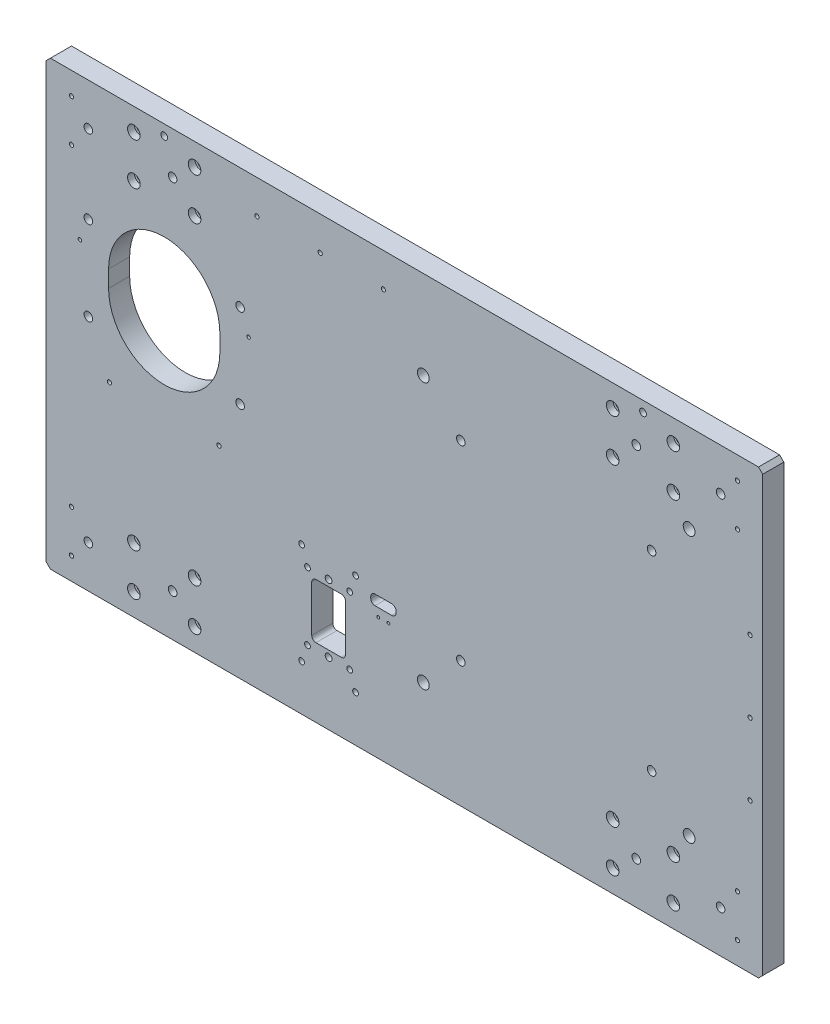
SolidWorks part; units mm, degrees
material "一般碳鋼"
ref_plane "前基準面" through (0, 0, 0) normal (0, 0, 1) x (1, 0, 0)
ref_plane "上基準面" through (0, 0, 0) normal (0, 1, 0) x (1, 0, 0)
ref_plane "右基準面" through (0, 0, 0) normal (1, 0, 0) x (0, 0, -1)
sketch "草圖1" plane through (0, 0, 0) normal (0, 0, 1) x (1, 0, 0)
  line L0 (0, 128.8443) -> (0, 0) construction
  line L1 (-605, 262.5) -> (245, 262.5)
  line L2 (-605, 262.5) -> (-605, -262.5)
  line L3 (-605, -262.5) -> (245, -262.5)
  line L4 (245, 262.5) -> (245, -262.5)
  line L5 (0, 0) -> (107.875, 0) construction
  dimension "D1" = 525
  dimension "D2" = 850
  dimension "D3" = 245
extrude "伸長1" add sketch "草圖1" along normal blind 25
hole_wizard "M16 螺紋孔1" positions "草圖4" profile "草圖3" tap size "M16" standard "GB"
sketch "草圖4" plane through (0, 0, 25) normal (0, 0, 1) x (1, 0, 0)
  line L1 (0, 0) -> (-181.3722, 181.3722) construction
  line L3 (0, 0) -> (0, 223) construction
  circle A0 centre (0, 0) radius 223
  point P1 (-157.6848, 157.6848)
  point P49 (257.6848, 137.6848)
  point P59 (157.6848, 157.6848)
  point P61 (157.6848, -157.6848)
  point P62 (-157.6848, -157.6848)
  dimension "D2" = 446
  dimension "D1" = 45
sketch "草圖3" plane through (-157.6848, 157.6848, 25) normal (1, 0, 0) x (0, -1, 0)
  line L0 (0, 0) -> (0, 42.206)
  line L1 (0, 42.206) -> (7, 38)
  line L2 (7, 38) -> (7, 0)
  line L5 (7, 0) -> (0, 0)
  line L10 (0, 42.206) -> (-7, 38) construction
  line L11 (0, -6.35) -> (0, 107.95) construction
  dimension "螺孔鑽直徑" = 14
  dimension "螺孔鑽深度" = 38
  dimension "導頭角度" = 118
cosmetic thread "鑽孔螺紋1" parameters "D1"=32, "D2"=16
cosmetic thread "鑽孔螺紋2" parameters "D1"=32, "D2"=16
cosmetic thread "鑽孔螺紋3" parameters "D1"=32, "D2"=16
cosmetic thread "鑽孔螺紋4" parameters "D1"=32, "D2"=16
hole_wizard "M12 螺紋孔2" positions "草圖51" profile "草圖50" tap size "M12" standard "GB" end condition up to next
sketch "草圖51" plane through (0, 0, 25) normal (0, 0, 1) x (1, 0, 0)
  line L0 (0, 0) -> (0, 119.7033) construction
  line L2 (0, 0) -> (-71.5063, 71.5063) construction
  circle A0 centre (0, 0) radius 160 construction
  point P1 (-113.1371, 113.1371)
  point P3 (113.1371, 113.1371)
  point P5 (-113.1371, -113.1371)
  point P7 (113.1371, -113.1371)
  dimension "D1" = 320
  dimension "D2" = 45
sketch "草圖50" plane through (-113.1371, 113.1371, 25) normal (1, 0, 0) x (0, -1, 0)
  line L0 (0, 0) -> (0, 25)
  line L1 (0, 25) -> (5.1, 25)
  line L2 (5.1, 25) -> (5.1, 0)
  line L5 (5.1, 0) -> (0, 0)
  line L11 (0, -6.35) -> (0, 107.95) construction
  dimension "貫穿螺孔鑽直徑" = 10.2
  dimension "貫穿螺孔鑽深度" = 25
cosmetic thread "鑽孔螺紋15" parameters "D2"=12
cosmetic thread "鑽孔螺紋16" parameters "D2"=12
cosmetic thread "鑽孔螺紋17" parameters "D2"=12
cosmetic thread "鑽孔螺紋18" parameters "D2"=12
hole_wizard "M8 六角承窩頭蓋螺釘的柱孔1" positions "草圖40" profile "草圖39" counterbore size "M8" standard "ISO" end condition through all
sketch "草圖40" plane through (0, 0, 25) normal (0, 0, 1) x (1, 0, 0)
  line L2 (-605, 0) -> (-201.2497, 0) construction
  line L3 (-605, 262.5) -> (-605, -262.5) construction
  line L5 (0, 0) -> (0, 249.5) construction
  point P1 (-501, 236)
  point P3 (-429, 236)
  point P5 (-501, 186)
  point P7 (-429, 186)
  point P22 (-429, -186)
  point P23 (-501, -186)
  point P24 (-429, -236)
  point P25 (-501, -236)
  dimension "D1" = 72
  dimension "D2" = 50
  dimension "D3" = 422
  dimension "D4" = 429
  dimension "D5" = 50
sketch "草圖39" plane through (-501, 236, 25) normal (1, 0, 0) x (0, -1, 0)
  line L0 (0, 0) -> (0, 25)
  line L1 (0, 25) -> (4.5, 25)
  line L3 (4.5, 25) -> (4.5, 8)
  line L4 (4.5, 8) -> (7.5, 8)
  line L5 (7.5, 8) -> (7.5, 0)
  line L7 (7.5, 0) -> (0, 0)
  line L11 (0, -6.35) -> (0, 107.95) construction
  dimension "貫穿孔直徑" = 9
  dimension "貫穿孔深度" = 25
  dimension "柱孔直徑" = 15
  dimension "柱孔深度" = 8
pattern_linear "直線複製排列1" count 2 spacing 568 along (1, 0, 0) of "M8 六角承窩頭蓋螺釘的柱孔1"
sketch "草圖41" plane through (0, 0, 25) normal (0, 0, 1) x (1, 0, 0)
  line L0 (-465, 80.5) -> (-465, 60.5) construction
  line L2 (-531, 80.5) -> (-531, 60.5)
  line L3 (-605, 262.5) -> (-605, -262.5) construction
  line L4 (-399, 80.5) -> (-399, 60.5)
  line L5 (-465, 174) -> (-465, 105.3673) construction
  line L6 (245, 262.5) -> (-605, 262.5) construction
  line L9 (-260, 70.5) -> (-220.5024, 70.5) construction
  arc A0 (-531, 80.5) -> (-399, 80.5) centre (-465, 80.5) cw
  arc A1 (-531, 60.5) -> (-399, 60.5) centre (-465, 60.5) ccw
  point P0 (-465, 70.5)
  dimension "D1" = 140
  dimension "D2" = 192
  dimension "D5" = 20
  dimension "D6" = 66
  dimension "D7" = 66
extrude "除料-伸長1" cut sketch "草圖41" against normal up to next
chamfer "導角1" distance 5 angle 45 4 edges at (-605, 262.5, 12.5) (245, 262.5, 12.5) (245, -262.5, 12.5) (-605, -262.5, 12.5)
hole_wizard "Ø5.0 (5) 直徑孔1" positions "草圖47" profile "草圖46" hole size "Ø5.0" standard "ISO" end condition up to next
sketch "草圖47" plane through (0, 0, 25) normal (0, 0, 1) x (1, 0, 0)
  line L1 (-501, 236) -> (-429, 236) construction
  line L13 (67, 236) -> (139, 236) construction
  point P0 (-465, 250)
  point P34 (103, 250)
  point P78 (103, 236)
  point P79 (-465, 236)
  dimension "D1" = 14
sketch "草圖46" plane through (-465, 250, 25) normal (1, 0, 0) x (0, -1, 0)
  line L0 (0, 0) -> (0, 25)
  line L1 (0, 25) -> (4, 25)
  line L2 (4, 25) -> (4, 0)
  line L5 (4, 0) -> (0, 0)
  line L11 (0, -6.35) -> (0, 107.95) construction
  dimension "貫穿孔直徑" = 8
  dimension "貫穿孔深度" = 25
hole_wizard "M6 螺紋孔2" positions "草圖55" profile "草圖54" tap size "M6" standard "GB" end condition up to next
sketch "草圖55" plane through (0, 0, 25) normal (0, 0, 1) x (1, 0, 0)
  line L2 (240, 262.5) -> (-600, 262.5) construction
  line L3 (-530, -35.5) -> (-400, -35.5) construction
  line L5 (-605, 257.5) -> (-605, -257.5) construction
  point P0 (-530, -35.5)
  point P1 (-400, -35.5)
  point P22 (-465, -35.5)
  dimension "D1" = 130
  dimension "D2" = 140
  dimension "D5" = 298
sketch "草圖54" plane through (-530, -35.5, 25) normal (1, 0, 0) x (0, -1, 0)
  line L0 (0, 0) -> (0, 25)
  line L1 (0, 25) -> (2.5, 25)
  line L2 (2.5, 25) -> (2.5, 0)
  line L5 (2.5, 0) -> (0, 0)
  line L11 (0, -6.35) -> (0, 107.95) construction
  dimension "貫穿螺孔鑽直徑" = 5
  dimension "貫穿螺孔鑽深度" = 25
cosmetic thread "鑽孔螺紋34" parameters "D2"=6
cosmetic thread "鑽孔螺紋35" parameters "D2"=6
hole_wizard "M6 螺紋孔3" positions "草圖65" profile "草圖64" tap size "M6" standard "GB" end condition up to next
sketch "草圖65" plane through (0, 0, 25) normal (0, 0, 1) x (1, 0, 0)
  line L0 (245, -257.5) -> (245, 257.5) construction
  line L2 (167.2421, 0) -> (230, 0) construction
  point P0 (230, 85)
  point P1 (230, -85)
  point P19 (230, 0)
  dimension "D1" = 15
  dimension "D2" = 170
sketch "草圖64" plane through (230, 85, 25) normal (1, 0, 0) x (0, -1, 0)
  line L0 (0, 0) -> (0, 25)
  line L1 (0, 25) -> (2.5, 25)
  line L2 (2.5, 25) -> (2.5, 0)
  line L5 (2.5, 0) -> (0, 0)
  line L11 (0, -6.35) -> (0, 107.95) construction
  dimension "貫穿螺孔鑽直徑" = 5
  dimension "貫穿螺孔鑽深度" = 25
cosmetic thread "鑽孔螺紋31" parameters "D2"=6
cosmetic thread "鑽孔螺紋32" parameters "D2"=6
cosmetic thread "鑽孔螺紋33" parameters "D2"=6
sketch "草圖69" plane through (0, 0, 25) normal (0, 0, 1) x (1, 0, 0)
  line L0 (-384.1039, -148) -> (-270, -148) construction
  line L1 (-285, -115.5) -> (-255, -115.5)
  line L2 (-290, -120.5) -> (-290, -175.5)
  line L3 (-285, -180.5) -> (-255, -180.5)
  line L4 (-250, -120.5) -> (-250, -175.5)
  line L5 (-270, -148) -> (-270, -221.1779) construction
  line L6 (-600, -262.5) -> (240, -262.5) construction
  line L7 (-605, 257.5) -> (-605, -257.5) construction
  arc A0 (-290, -120.5) -> (-285, -115.5) centre (-285, -120.5) cw
  arc A1 (-250, -120.5) -> (-255, -115.5) centre (-255, -120.5) ccw
  arc A2 (-250, -175.5) -> (-255, -180.5) centre (-255, -175.5) cw
  arc A3 (-290, -175.5) -> (-285, -180.5) centre (-285, -175.5) ccw
  point P15 (-250, -115.5)
  point P18 (-250, -180.5)
  point P21 (-290, -180.5)
  dimension "D5" = 5
  dimension "D1" = 114.5
  dimension "D2" = 335
  dimension "D3" = 40
  dimension "D4" = 65
extrude "除料-伸長3" cut sketch "草圖69" against normal up to next
sketch "草圖70" plane through (0, 0, 25) normal (0, 0, 1) x (1, 0, 0)
  line L0 (-214.3273, -101.5) -> (-177.0507, -101.5) construction
  line L1 (-215, -95.5) -> (-195, -95.5)
  line L2 (-220, -100.5) -> (-220, -102.5)
  line L3 (-215, -107.5) -> (-195, -107.5)
  line L4 (-190, -100.5) -> (-190, -102.5)
  line L5 (-205, -99.7891) -> (-205, -128.2663) construction
  line L7 (-605, 257.5) -> (-605, -257.5) construction
  line L9 (-600, -262.5) -> (240, -262.5) construction
  arc A0 (-220, -100.5) -> (-215, -95.5) centre (-215, -100.5) cw
  arc A1 (-215, -107.5) -> (-220, -102.5) centre (-215, -102.5) cw
  arc A2 (-190, -102.5) -> (-195, -107.5) centre (-195, -102.5) cw
  arc A3 (-190, -100.5) -> (-195, -95.5) centre (-195, -100.5) ccw
  point P12 (-220, -95.5)
  point P17 (-190, -107.5)
  point P20 (-190, -95.5)
  dimension "D4" = 5
  dimension "D1" = 12
  dimension "D2" = 30
  dimension "D3" = 161
  dimension "D5" = 400
extrude "除料-伸長4" cut sketch "草圖70" against normal up to next
hole_wizard "M4 螺紋孔1" positions "草圖73" profile "草圖72" tap size "M4" standard "GB" end condition up to next
sketch "草圖73" plane through (-9.3244, -29.0893, 25) normal (0, 0, 1) x (1, 0, 0)
  line L4 (-195.6756, -78.4107) -> (-195.6756, -132.1764) construction
  line L6 (-205.6756, -78.4107) -> (-185.6756, -78.4107) construction
  point P0 (-201.6756, -88.4107)
  point P1 (-189.6756, -88.4107)
  dimension "D1" = 12
  dimension "D2" = 10
cosmetic thread "鑽孔螺紋36" parameters "D2"=4
cosmetic thread "鑽孔螺紋37" parameters "D2"=4
sketch "草圖72" plane through (-211, -117.5, 25) normal (1, 0, 0) x (0, -1, 0)
  line L0 (0, 0) -> (0, 25)
  line L1 (0, 25) -> (1.65, 25)
  line L2 (1.65, 25) -> (1.65, 0)
  line L5 (1.65, 0) -> (0, 0)
  line L11 (0, -6.35) -> (0, 107.95) construction
  dimension "貫穿螺孔鑽直徑" = 3.3
  dimension "貫穿螺孔鑽深度" = 25
hole_wizard "M12 螺紋孔3" positions "3D草圖1" profile "草圖74" tap size "M12" standard "GB" end condition up to next
sketch3d "3D草圖1"
  line L0 (-605, 257.5, 25) -> (-605, -257.5, 25) construction
  line L1 (240, 262.5, 25) -> (-600, 262.5, 25) construction
  point P0 (-555, 119.5, 25)
  point P2 (-555, 19.5, 25)
  point P4 (-375, 119.5, 25)
  point P6 (-375, 19.5, 25)
  dimension "D1" = 180
  dimension "D2" = 100
  dimension "D3" = 50
  dimension "D4" = 143
sketch "草圖74" plane through (-555, 119.5, 25) normal (1, 0, 0) x (0, -1, 0)
  line L0 (0, 0) -> (0, 25)
  line L1 (0, 25) -> (5.1, 25)
  line L2 (5.1, 25) -> (5.1, 0)
  line L5 (5.1, 0) -> (0, 0)
  line L11 (0, -6.35) -> (0, 107.95) construction
  dimension "貫穿螺孔鑽直徑" = 10.2
  dimension "貫穿螺孔鑽深度" = 25
cosmetic thread "鑽孔螺紋38" parameters "D2"=12
cosmetic thread "鑽孔螺紋39" parameters "D2"=12
cosmetic thread "鑽孔螺紋40" parameters "D2"=12
cosmetic thread "鑽孔螺紋41" parameters "D2"=12
hole_wizard "M5 螺紋孔1" positions "3D草圖2" profile "草圖75" tap size "M5" standard "GB" end condition up to next
sketch3d "3D草圖2"
  line L0 (240, 262.5, 0) -> (-600, 262.5, 0) construction
  line L1 (-605, 257.5, 0) -> (-605, -257.5, 0) construction
  point P0 (-565, 93.5, 0)
  point P2 (-365, 93.5, 0)
  dimension "D1" = 200
  dimension "D2" = 169
  dimension "D3" = 40
sketch "草圖75" plane through (-565, 93.5, 0) normal (1, 0, 0) x (0, 1, 0)
  line L0 (0, 0) -> (0, 25)
  line L1 (0, 25) -> (2.1, 25)
  line L2 (2.1, 25) -> (2.1, 0)
  line L5 (2.1, 0) -> (0, 0)
  line L11 (0, -6.35) -> (0, 107.95) construction
  dimension "貫穿螺孔鑽直徑" = 4.2
  dimension "貫穿螺孔鑽深度" = 25
cosmetic thread "鑽孔螺紋42" parameters "D2"=5
cosmetic thread "鑽孔螺紋43" parameters "D2"=5
hole_wizard "M8 螺紋孔1" positions "3D草圖3" profile "草圖76" tap size "M8" standard "GB" end condition up to next
sketch3d "3D草圖3"
  line L0 (-302, -88, 35) -> (-302, -88, 43) construction
  line L1 (-302, -208, 35) -> (-302, -208, 43) construction
  line L2 (-238, -208, 35) -> (-238, -208, 43) construction
  line L3 (-238, -88, 35) -> (-238, -88, 43) construction
  point P0 (-302, -88, 25)
  point P2 (-302, -208, 25)
  point P4 (-238, -208, 25)
  point P6 (-238, -88, 25)
sketch "草圖76" plane through (-302, -88, 25) normal (1, 0, 0) x (0, -1, 0)
  line L0 (0, 0) -> (0, 25)
  line L1 (0, 25) -> (3.4, 25)
  line L2 (3.4, 25) -> (3.4, 0)
  line L5 (3.4, 0) -> (0, 0)
  line L11 (0, -6.35) -> (0, 107.95) construction
  dimension "貫穿螺孔鑽直徑" = 6.8
  dimension "貫穿螺孔鑽深度" = 25
cosmetic thread "鑽孔螺紋44" parameters "D2"=8
cosmetic thread "鑽孔螺紋45" parameters "D2"=8
cosmetic thread "鑽孔螺紋46" parameters "D2"=8
cosmetic thread "鑽孔螺紋47" parameters "D2"=8
hole_wizard "M8 螺紋孔2" positions "草圖79" profile "草圖78" tap size "M8" standard "GB" end condition up to next
sketch "草圖79" plane through (0, 0, 0) normal (0, 0, -1) x (-1, 0, 0)
  point P0 (295, -108)
  point P1 (245, -108)
  point P3 (295, -188)
  point P5 (245, -188)
sketch "草圖78" plane through (-295, -108, 0) normal (1, 0, 0) x (0, 1, 0)
  line L0 (0, 0) -> (0, 25)
  line L1 (0, 25) -> (3.4, 25)
  line L2 (3.4, 25) -> (3.4, 0)
  line L5 (3.4, 0) -> (0, 0)
  line L11 (0, -6.35) -> (0, 107.95) construction
  dimension "貫穿螺孔鑽直徑" = 6.8
  dimension "貫穿螺孔鑽深度" = 25
cosmetic thread "鑽孔螺紋48" parameters "D2"=8
cosmetic thread "鑽孔螺紋49" parameters "D2"=8
cosmetic thread "鑽孔螺紋50" parameters "D2"=8
cosmetic thread "鑽孔螺紋51" parameters "D2"=8
hole_wizard "Ø8.0 (8) 直徑孔1" positions "草圖81" profile "草圖80" hole size "Ø8.0" standard "ISO" end condition up to next
sketch "草圖81" plane through (0, 0, 0) normal (0, 0, -1) x (-1, 0, 0)
  point P0 (270, -108)
  point P1 (270, -188)
sketch "草圖80" plane through (-270, -108, 0) normal (1, 0, 0) x (0, 1, 0)
  line L0 (0, 0) -> (0, 25)
  line L1 (0, 25) -> (4, 25)
  line L2 (4, 25) -> (4, 0)
  line L5 (4, 0) -> (0, 0)
  line L11 (0, -6.35) -> (0, 107.95) construction
  dimension "貫穿孔直徑" = 8
  dimension "貫穿孔深度" = 25
hole_wizard "M12 螺紋孔4" positions "草圖83" profile "草圖82" tap size "M12" standard "GB" end condition up to next
sketch "草圖83" plane through (0, 0, 25) normal (0, 0, 1) x (1, 0, 0)
  line L0 (-605, 257.5) -> (-605, -257.5) construction
  line L1 (240, 262.5) -> (-600, 262.5) construction
  line L2 (-600, -262.5) -> (240, -262.5) construction
  line L3 (245, -257.5) -> (245, 257.5) construction
  point P0 (-555, 212.5)
  point P1 (-455, 212.5)
  point P3 (-555, -212.5)
  point P5 (-455, -212.5)
  point P14 (95, 212.5)
  point P16 (195, 212.5)
  point P18 (95, -212.5)
  point P20 (195, -212.5)
  dimension "D1" = 100
  dimension "D2" = 50
  dimension "D3" = 50
  dimension "D4" = 50
  dimension "D5" = 100
  dimension "D6" = 50
sketch "草圖82" plane through (-555, 212.5, 25) normal (1, 0, 0) x (0, -1, 0)
  line L0 (0, 0) -> (0, 25)
  line L1 (0, 25) -> (5.1, 25)
  line L2 (5.1, 25) -> (5.1, 0)
  line L5 (5.1, 0) -> (0, 0)
  line L11 (0, -6.35) -> (0, 107.95) construction
  dimension "貫穿螺孔鑽直徑" = 10.2
  dimension "貫穿螺孔鑽深度" = 25
cosmetic thread "鑽孔螺紋52" parameters "D2"=12
cosmetic thread "鑽孔螺紋53" parameters "D2"=12
cosmetic thread "鑽孔螺紋54" parameters "D2"=12
cosmetic thread "鑽孔螺紋55" parameters "D2"=12
cosmetic thread "鑽孔螺紋56" parameters "D2"=12
cosmetic thread "鑽孔螺紋57" parameters "D2"=12
cosmetic thread "鑽孔螺紋58" parameters "D2"=12
cosmetic thread "鑽孔螺紋59" parameters "D2"=12
hole_wizard "M6 螺紋孔4" positions "草圖85" profile "草圖84" tap size "M6" standard "GB" end condition up to next
sketch "草圖85" plane through (0, 0, 25) normal (0, 0, 1) x (1, 0, 0)
  line L0 (-501, 236) -> (-501, 186) construction
  line L2 (-501, 211) -> (-592.1267, 211) construction
  line L4 (-501, -236) -> (-501, -186) construction
  line L6 (-501, -211) -> (-583.9687, -211) construction
  line L8 (-605, 257.5) -> (-605, -257.5) construction
  line L9 (245, -257.5) -> (245, 257.5) construction
  point P0 (-575, 186)
  point P1 (-575, 236)
  point P3 (-575, -186)
  point P5 (-575, -236)
  point P7 (215, 236)
  point P9 (215, 186)
  point P11 (215, -186)
  point P13 (215, -236)
  dimension "D1" = 50
  dimension "D2" = 50
  dimension "D3" = 30
  dimension "D4" = 30
sketch "草圖84" plane through (-575, 186, 25) normal (1, 0, 0) x (0, -1, 0)
  line L0 (0, 0) -> (0, 25)
  line L1 (0, 25) -> (2.5, 25)
  line L2 (2.5, 25) -> (2.5, 0)
  line L5 (2.5, 0) -> (0, 0)
  line L11 (0, -6.35) -> (0, 107.95) construction
  dimension "貫穿螺孔鑽直徑" = 5
  dimension "貫穿螺孔鑽深度" = 25
cosmetic thread "鑽孔螺紋60" parameters "D2"=6
cosmetic thread "鑽孔螺紋61" parameters "D2"=6
cosmetic thread "鑽孔螺紋62" parameters "D2"=6
cosmetic thread "鑽孔螺紋63" parameters "D2"=6
cosmetic thread "鑽孔螺紋64" parameters "D2"=6
cosmetic thread "鑽孔螺紋65" parameters "D2"=6
cosmetic thread "鑽孔螺紋66" parameters "D2"=6
cosmetic thread "鑽孔螺紋67" parameters "D2"=6
hole_wizard "M6 螺紋孔5" positions "草圖87" profile "草圖86" tap size "M6" standard "GB" end condition up to next
sketch "草圖87" plane through (0, 0, 25) normal (0, 0, 1) x (1, 0, 0)
  line L0 (240, 262.5) -> (-600, 262.5) construction
  line L1 (-605, 257.5) -> (-605, -257.5) construction
  point P0 (-280, 222.5)
  point P1 (-205, 222.5)
  point P3 (-355, 222.5)
  dimension "D1" = 75
  dimension "D2" = 75
  dimension "D3" = 40
  dimension "D4" = 250
sketch "草圖86" plane through (-280, 222.5, 25) normal (1, 0, 0) x (0, -1, 0)
  line L0 (0, 0) -> (0, 25)
  line L1 (0, 25) -> (2.5, 25)
  line L2 (2.5, 25) -> (2.5, 0)
  line L5 (2.5, 0) -> (0, 0)
  line L11 (0, -6.35) -> (0, 107.95) construction
  dimension "貫穿螺孔鑽直徑" = 5
  dimension "貫穿螺孔鑽深度" = 25
cosmetic thread "鑽孔螺紋68" parameters "D2"=6
cosmetic thread "鑽孔螺紋69" parameters "D2"=6
cosmetic thread "鑽孔螺紋70" parameters "D2"=6
